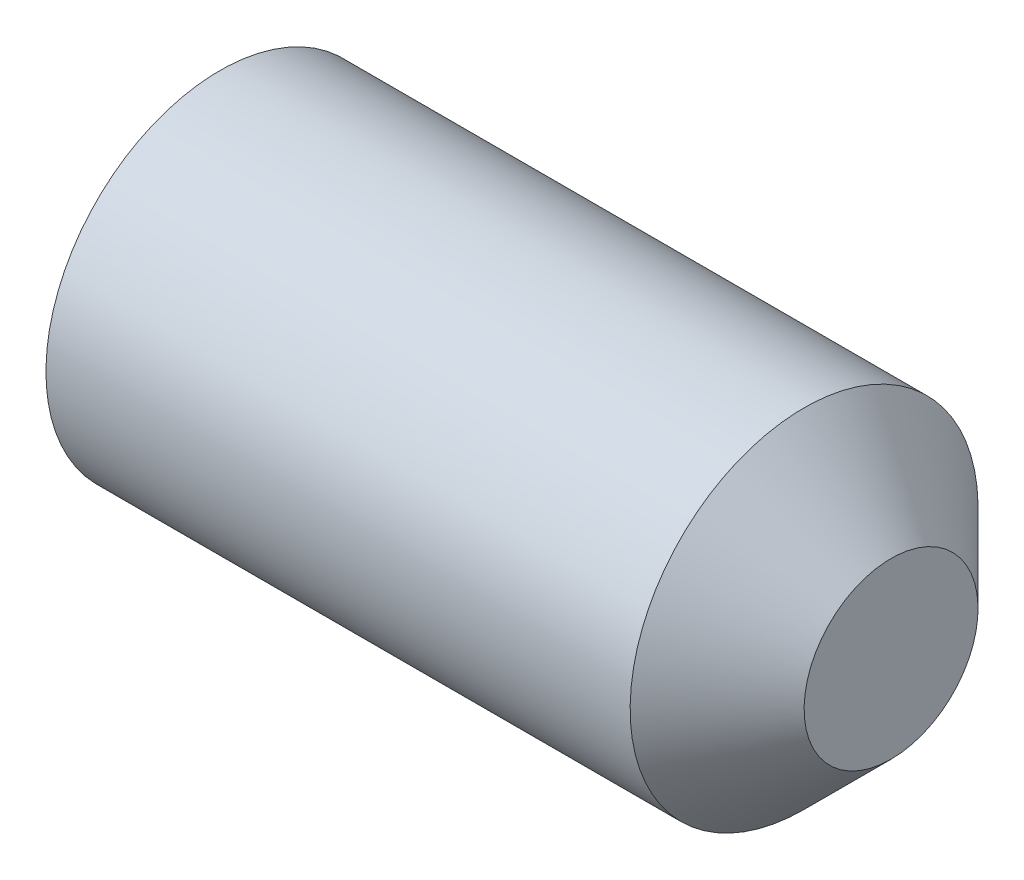
SolidWorks part; units mm, degrees
ref_plane "Front Plane" through (0, 0, 0) normal (0, 0, 1) x (1, 0, 0)
ref_plane "Top Plane" through (0, 0, 0) normal (0, 1, 0) x (1, 0, 0)
ref_plane "Right Plane" through (0, 0, 0) normal (1, 0, 0) x (0, 0, -1)
ref_plane "Plane1" through (0, 0, 0) normal (0, 0, 1) x (1, 0, 0)
sketch "Sketch1" plane through (0, 0, 0) normal (0, 0, 1) x (1, 0, 0)
  line L0 (4, 0) -> (4, -0.5)
  line L1 (4, -0.5) -> (3.5, -1)
  line L2 (3.5, -1) -> (0.1417, -1)
  line L3 (0.1417, -1) -> (0, -0.7545)
  line L4 (0, -0.7545) -> (0, -0.5196)
  line L5 (0, -0.5196) -> (0.3, 0)
  line L6 (0.3, 0) -> (4, 0)
  line L7 (0.3, 0) -> (4, 0) construction
revolve "Revolve1" add sketch "Sketch1" angle 360 about L7
ref_plane "Plane2" through (0, 0, 0) normal (1, 0, 0) x (0, 0, -1)
sketch "Sketch2" plane through (0, 0, 0) normal (1, 0, 0) x (0, 0, -1)
  line L0 (-0.5196, 0) -> (-0.2598, -0.45)
  line L1 (-0.2598, -0.45) -> (0.2598, -0.45)
  line L2 (0.2598, -0.45) -> (0.5196, 0)
  line L3 (0.5196, 0) -> (0.2598, 0.45)
  line L4 (0.2598, 0.45) -> (-0.2598, 0.45)
  line L5 (-0.2598, 0.45) -> (-0.5196, 0)
extrude "Cut-Extrude1" cut sketch "Sketch2" along normal blind 1.7
